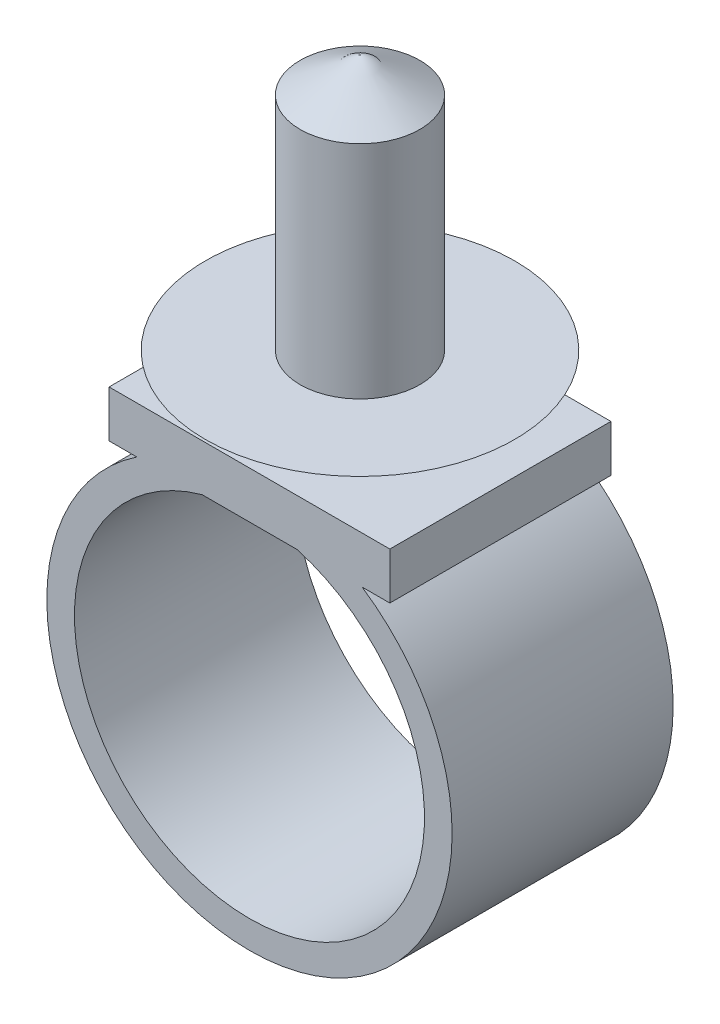
SolidWorks part; units mm, degrees
ref_plane "Front Plane" through (0, 0, 0) normal (0, 0, 1) x (1, 0, 0)
ref_plane "Top Plane" through (0, 0, 0) normal (0, 1, 0) x (1, 0, 0)
ref_plane "Right Plane" through (0, 0, 0) normal (1, 0, 0) x (0, 0, -1)
sketch "Sketch1" plane through (0, 0, 0) normal (0, 0, 1) x (1, 0, 0)
  circle A0 centre (0, 0) radius 9.5
  circle A1 centre (0, 0) radius 11
extrude "Boss-Extrude1" add sketch "Sketch1" along normal blind 12
ref_plane "Plane1" through (0, 9.144, 0) normal (0, 1, 0) x (1, 0, 0)
sketch "Sketch2" plane through (0, 9.144, 0) normal (0, 1, 0) x (1, 0, 0)
  line L0 (0, 0) -> (7.62, 0)
  line L1 (11, 0) -> (-11, 0) construction
  line L2 (7.62, 0) -> (7.62, -12)
  line L3 (-11, -12) -> (11, -12) construction
  line L4 (7.62, -12) -> (-7.62, -12)
  line L5 (-7.62, -12) -> (-7.62, 0)
  line L6 (9.5, 0) -> (-9.5, 0) construction
  line L7 (-7.62, 0) -> (0, 0)
  dimension "D1" = 7.62
  dimension "D2" = 7.62
extrude "Boss-Extrude2" add sketch "Sketch2" along normal blind 2.54
sketch "Sketch3" plane through (0, 11.684, 0) normal (0, 1, 0) x (1, 0, 0)
  line L0 (-7.62, 0) -> (7.62, -12) construction
  circle A0 centre (0, -6) radius 4
extrude "Boss-Extrude3" add sketch "Sketch3" along normal blind 2.54 draft 60 draft outward yes
sketch "Sketch4" plane through (0, 14.224, 0) normal (0, 1, 0) x (1, 0, 0)
  circle A0 centre (0, -6) radius 3.25
extrude "Boss-Extrude4" add sketch "Sketch4" along normal blind 12
sketch "Sketch5" plane through (0, 26.224, 0) normal (0, 1, 0) x (1, 0, 0)
  circle A0 centre (0, -6) radius 3.25
extrude "Boss-Extrude5" add sketch "Sketch5" along normal blind 3.05 draft 60
